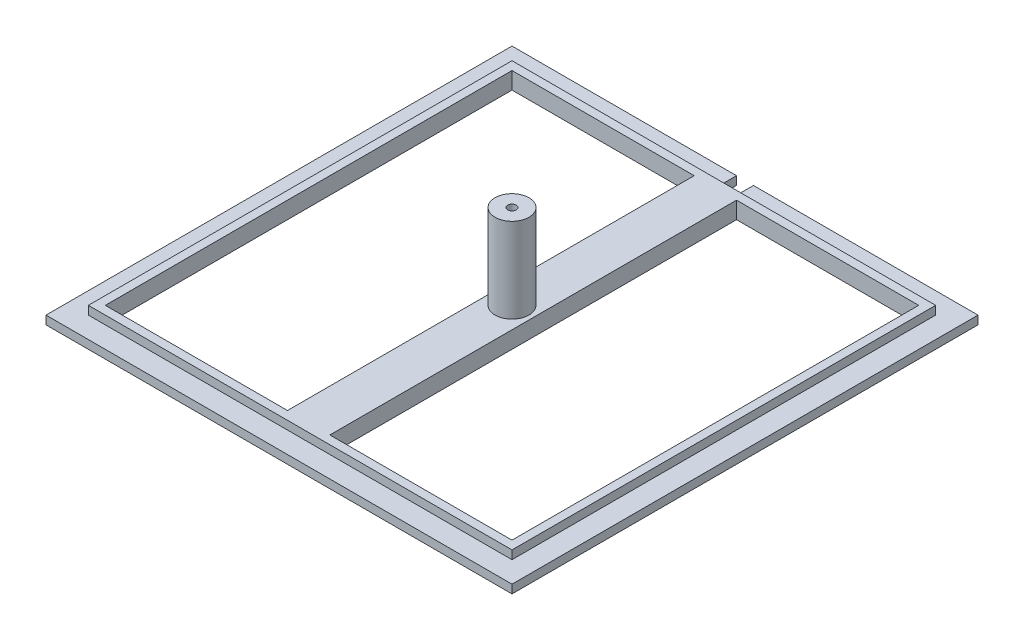
SolidWorks part; units mm, degrees
ref_plane "Alzado" through (0, 0, 0) normal (0, 0, 1) x (1, 0, 0)
ref_plane "Planta" through (0, 0, 0) normal (0, 1, 0) x (1, 0, 0)
ref_plane "Vista lateral" through (0, 0, 0) normal (1, 0, 0) x (0, 0, -1)
sketch "Croquis1" plane through (0, 0, 0) normal (0, 1, 0) x (1, 0, 0)
  line L0 (-5, -5) -> (-5, 105)
  line L1 (0, 0) -> (100, 0)
  line L2 (0, 0) -> (0, 100)
  line L3 (0, 100) -> (100, 100)
  line L4 (100, 0) -> (100, 100)
  line L5 (-5, 105) -> (105, 105)
  line L6 (105, -5) -> (105, 105)
  line L7 (-5, -5) -> (105, -5)
  dimension "D1" = 100
  dimension "D2" = 5
extrude "Saliente-Extruir1" add sketch "Croquis1" along normal blind 2
sketch "Croquis2" plane through (0, 0, 0) normal (0, -1, 0) x (1, 0, 0)
  line L0 (100, -100) -> (0, -100) construction
  line L1 (100, 0) -> (100, -100) construction
  line L2 (0, 0) -> (100, 0) construction
  line L3 (0, -100) -> (0, 0) construction
  line L4 (100, -100) -> (0, -100)
  line L5 (100, 0) -> (100, -100)
  line L6 (0, 0) -> (100, 0)
  line L7 (0, -100) -> (0, 0)
  line L8 (98, -98) -> (2, -98)
  line L9 (2, -98) -> (2, -2)
  line L10 (2, -2) -> (98, -2)
  line L11 (98, -2) -> (98, -98)
  dimension "D1" = 2
extrude "Saliente-Extruir2" add sketch "Croquis2" against normal blind 4
sketch "Croquis3" plane through (0, 0, 0) normal (0, -1, 0) x (1, 0, 0)
  line L0 (98, -2) -> (2, -2) construction
  line L1 (45, -2) -> (55, -2)
  line L2 (45, -2) -> (45, -98)
  line L3 (45, -98) -> (55, -98)
  line L4 (55, -2) -> (55, -98)
  line L5 (2, -98) -> (98, -98) construction
  line L6 (50, -2) -> (50, 5) construction
  line L7 (-5, 5) -> (105, 5) construction
  dimension "D1" = 10
extrude "Saliente-Extruir3" add sketch "Croquis3" against normal blind 4
sketch "Croquis4" plane through (0, 4, 0) normal (0, 1, 0) x (1, 0, 0)
  line L0 (45, 50) -> (55, 50) construction
  line L1 (45, 2) -> (45, 98) construction
  line L2 (55, 98) -> (55, 2) construction
  circle A0 centre (50, 50) radius 1
  circle A1 centre (50, 50) radius 4
  dimension "D1" = 2
  dimension "D2" = 8
extrude "Saliente-Extruir4" add sketch "Croquis4" along normal blind 20
sketch "Croquis5" plane through (0, 4, 0) normal (0, 1, 0) x (1, 0, 0)
  circle A1 centre (50, 50) radius 1
  circle A2 centre (50, 50) radius 1
  dimension "D1" = 0
extrude "Cortar-Extruir1" cut sketch "Croquis5" against normal blind 20
sketch "Croquis6" plane through (0, 0, -105) normal (0, 0, -1) x (-1, 0, 0)
  line L2 (-105, 0) -> (5, 0) construction
  line L3 (-52, 0) -> (-48, 0)
  line L4 (-52, 0) -> (-52, 2)
  line L5 (-52, 2) -> (-48, 2)
  line L6 (-48, 0) -> (-48, 2)
  line L7 (-50, 2) -> (-50, 4) construction
  line L8 (0, 4) -> (-100, 4) construction
  dimension "D1" = 4
  dimension "D2" = 2
extrude "Cortar-Extruir4" cut sketch "Croquis6" against normal blind 55
